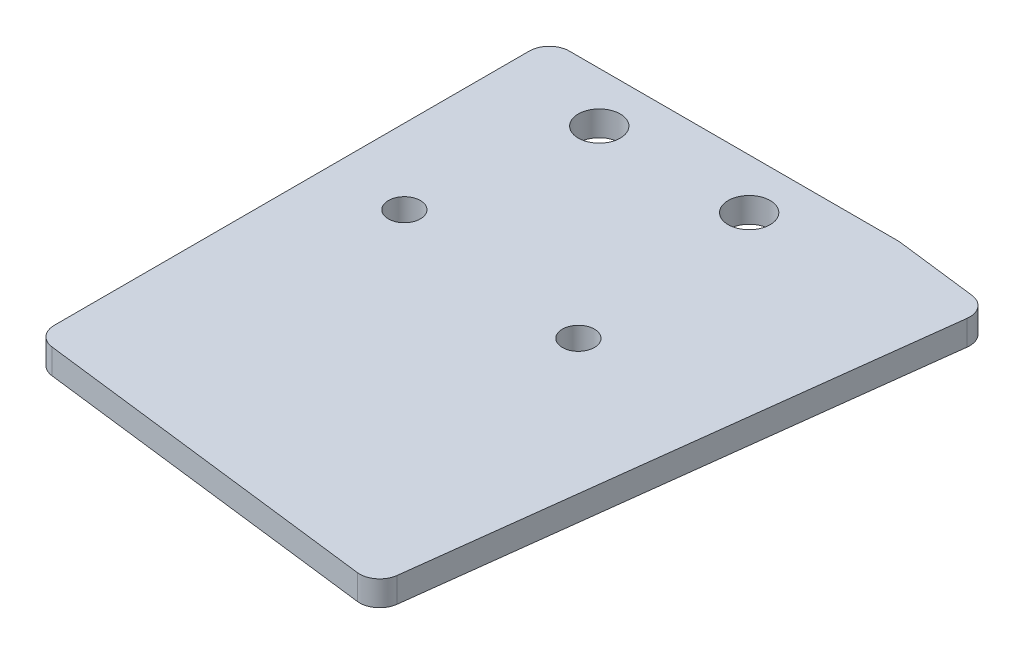
SolidWorks part; units mm, degrees
material "Thornel Mat VMA"
ref_plane "前视基准面" through (0, 0, 0) normal (0, 0, 1) x (1, 0, 0)
ref_plane "上视基准面" through (0, 0, 0) normal (0, 1, 0) x (1, 0, 0)
ref_plane "右视基准面" through (0, 0, 0) normal (1, 0, 0) x (0, 0, -1)
sketch "草图1" plane through (0, 0, 0) normal (0, 1, 0) x (1, 0, 0)
  line L0 (-7.5, 0) -> (7.5, 0) construction
  line L1 (-17.5, 5) -> (17.5, 5)
  line L2 (-17.5, 5) -> (-17.5, -5)
  line L3 (-17.5, -5) -> (17.5, -5)
  line L4 (17.5, 5) -> (17.5, -5)
  line L5 (-17.5, 5) -> (17.5, -5) construction
  line L6 (-17.5, -5) -> (17.5, 5) construction
  circle A0 centre (-7.5, 0) radius 2.1
  circle A1 centre (7.5, 0) radius 2.1
  point P0 (0, 0)
  dimension "D4" = 4.2
  dimension "D1" = 15
  dimension "D2" = 10
  dimension "D3" = 10
extrude "凸台-拉伸1" add sketch "草图1" along normal blind 2.5
sketch "草图3" plane through (0, 2.5, 0) normal (0, 1, 0) x (1, 0, 0)
  line L0 (-10, -17) -> (9.8509, -19.4374) construction
  line L1 (-17.5, -5) -> (17.5, -5)
  line L2 (-17.5, -5) -> (-17.5, -46.3044)
  line L4 (17.5, -5) -> (17.5, -50.6019)
  line L5 (-17.5, -5) -> (17.5, -5) construction
  line L6 (17.5, -50.6019) -> (-17.5, -46.3044)
  circle A0 centre (-10, -17) radius 1.6
  circle A1 centre (9.8509, -19.4374) radius 1.6
  dimension "D6" = 3.2
  dimension "D1" = 20
  dimension "D2" = 83
  dimension "D3" = 12
  dimension "D4" = 10
  dimension "D5" = 30
extrude "凸台-拉伸2" add sketch "草图3" against normal up to surface (2.5 mm away) contours L1 L4 L6 L2
sketch "草图4" plane through (0, 2.5, 0) normal (0, 1, 0) x (1, 0, 0)
  line L0 (21.083, -51.0418) -> (27.8087, 3.7343)
  line L1 (27.8087, 3.7343) -> (17.5, 5)
  line L2 (17.5, 5) -> (17.5, -50.6019)
  line L3 (17.5, -50.6019) -> (21.083, -51.0418)
  line L4 (-17.5, -46.3044) -> (17.5, -50.6019) construction
  line L5 (25.1047, -18.2878) -> (24.3735, -24.2431) construction
extrude "凸台-拉伸3" add sketch "草图4" against normal up to surface (2.5 mm away) up to face at (0, 0, 21.7266)
fillet "圆角1" radius 2 5 edges at (-17.5, 1.25, -5) (-17.5, 1.25, 46.3044) (21.083, 1.25, 51.0418) (17.5, 1.25, -5) (27.8087, 1.25, -3.7343)
